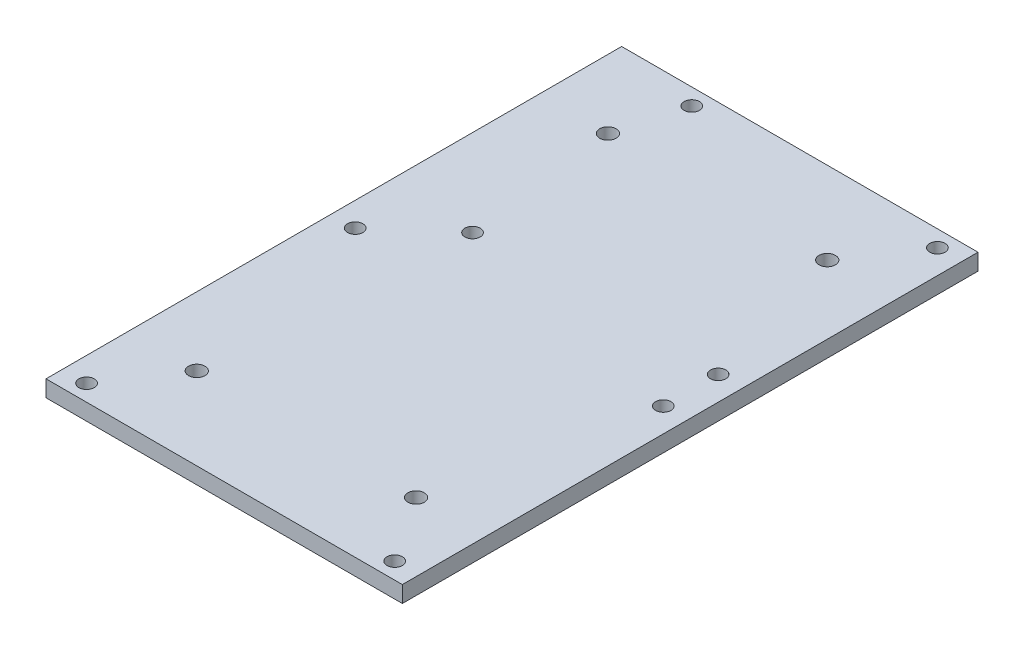
SolidWorks part; units mm, degrees
material "山毛榉"
ref_plane "前视基准面" through (0, 0, 0) normal (0, 0, 1) x (1, 0, 0)
ref_plane "上视基准面" through (0, 0, 0) normal (0, 1, 0) x (1, 0, 0)
ref_plane "右视基准面" through (0, 0, 0) normal (1, 0, 0) x (0, 0, -1)
sketch "草图1" plane through (0, 0, 0) normal (0, 1, 0) x (1, 0, 0)
  line L1 (-32.5, 52.5) -> (32.5, 52.5)
  line L2 (-32.5, 52.5) -> (-32.5, -52.5)
  line L3 (-32.5, -52.5) -> (32.5, -52.5)
  line L4 (32.5, 52.5) -> (32.5, -52.5)
  line L5 (0, -52.5) -> (0, 52.5) construction
  line L6 (-32.5, 0) -> (32.5, 0) construction
  point P0 (0, 0)
  dimension "D1" = 65
  dimension "D2" = 105
extrude "凸台-拉伸1" add sketch "草图1" along normal blind 3
sketch "草图2" plane through (0, 3, 0) normal (0, 1, 0) x (1, 0, 0)
  line L0 (-32.5, -52.5) -> (32.5, -52.5) construction
  line L1 (-28.1, -49.5) -> (28.1, -49.5) construction
  line L2 (-28.1, -49.5) -> (-28.1, -0.5) construction
  line L3 (-28.1, -0.5) -> (28.1, -0.5) construction
  line L4 (28.1, -49.5) -> (28.1, -0.5) construction
  line L5 (0, -0.5) -> (0, -49.5) construction
  line L6 (-28.1, -25) -> (28.1, -25) construction
  circle A0 centre (-28.1, -49.5) radius 1.4
  circle A1 centre (28.1, -49.5) radius 1.4
  circle A2 centre (28.1, -0.5) radius 1.4
  circle A3 centre (-28.1, -0.5) radius 1.4
  point P0 (0, -25)
  dimension "D1" = 2.8
  dimension "D2" = 2
  dimension "D4" = 56.2
  dimension "D5" = 49
  dimension "D6" = 3
  dimension "D3" = 2
extrude "切除-拉伸1" cut sketch "草图2" against normal through all
sketch "草图3" plane through (0, 3, 0) normal (0, 1, 0) x (1, 0, 0)
  line L0 (32.5, 52.5) -> (-32.5, 52.5) construction
  line L1 (-16.7, 49.5) -> (28.1, 49.5) construction
  line L2 (-16.7, 49.5) -> (-16.7, 9.5) construction
  line L3 (-16.7, 9.5) -> (28.1, 9.5) construction
  line L4 (28.1, 49.5) -> (28.1, 9.5) construction
  line L5 (5.7, 9.5) -> (5.7, 49.5) construction
  line L6 (-16.7, 29.5) -> (28.1, 29.5) construction
  line L7 (28.1, -49.5) -> (28.1, -0.5) construction
  circle A0 centre (-16.7, 9.5) radius 1.4
  circle A1 centre (28.1, 9.5) radius 1.4
  circle A2 centre (28.1, 49.5) radius 1.4
  circle A3 centre (-16.7, 49.5) radius 1.4
  point P0 (5.7, 29.5)
  dimension "D4" = 2.8
  dimension "D1" = 44.8
  dimension "D2" = 40
  dimension "D3" = 3
  dimension "D5" = 2
  dimension "D6" = 2
extrude "切除-拉伸2" cut sketch "草图3" against normal through all
sketch "草图6" plane through (0, 3, 0) normal (0, 1, 0) x (1, 0, 0)
  line L1 (-20, -37.5) -> (20, -37.5) construction
  line L2 (-20, -37.5) -> (-20, 37.5) construction
  line L3 (-20, 37.5) -> (20, 37.5) construction
  line L4 (20, -37.5) -> (20, 37.5) construction
  line L5 (0, 37.5) -> (0, -37.5) construction
  line L6 (-20, 0) -> (20, 0) construction
  circle A0 centre (-20, -37.5) radius 1.5
  circle A1 centre (20, -37.5) radius 1.5
  circle A2 centre (20, 37.5) radius 1.5
  circle A3 centre (-20, 37.5) radius 1.5
  point P0 (0, 0)
  dimension "D3" = 3
  dimension "D1" = 75
  dimension "D2" = 40
  dimension "D4" = 2
  dimension "D5" = 2
extrude "切除-拉伸5" cut sketch "草图6" against normal through all
